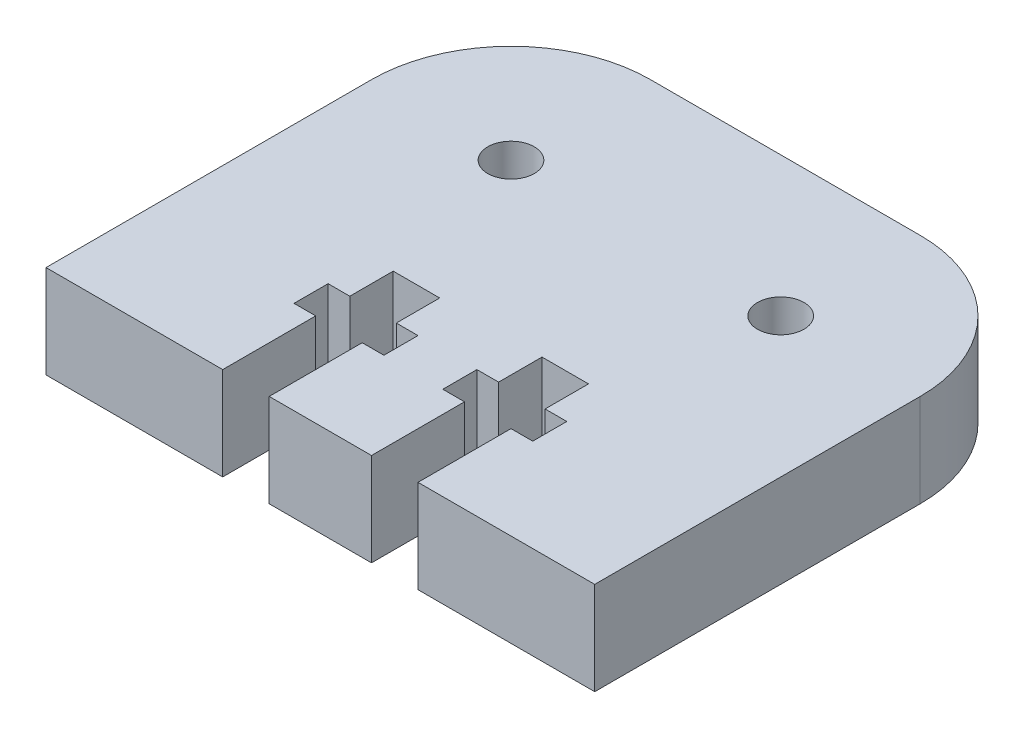
SolidWorks part; units mm, degrees
ref_plane "Front Plane" through (0, 0, 0) normal (0, 0, 1) x (1, 0, 0)
ref_plane "Top Plane" through (0, 0, 0) normal (0, 1, 0) x (1, 0, 0)
ref_plane "Right Plane" through (0, 0, 0) normal (1, 0, 0) x (0, 0, -1)
sketch "Sketch1" plane through (0, 0, 0) normal (0, 1, 0) x (1, 0, 0)
  line L0 (-55, 0) -> (55, 0) construction
  line L1 (-17.7, 15) -> (0, 15)
  line L2 (-17.7, 15) -> (-17.7, -15)
  line L3 (-17.7, -15) -> (-6.3, -15)
  line L4 (0, 15) -> (0, -15)
  line L5 (-17.7, 15) -> (0, -15) construction
  line L6 (-17.7, -15) -> (0, 15) construction
  line L7 (0, -55) -> (0, 55) construction
  line L8 (-4.8, -7.9) -> (-4.8, -4) construction
  line L9 (-6.3, -4) -> (-3.3, -4)
  line L10 (-6.3, -4) -> (-6.3, -6.8)
  line L12 (-3.3, -4) -> (-3.3, -6.8)
  line L13 (-6.3, -4) -> (-3.3, -15) construction
  line L14 (-6.3, -15) -> (-3.3, -4) construction
  line L15 (-7.7, -9) -> (-6.3, -9)
  line L16 (-7.7, -9) -> (-7.7, -6.8)
  line L17 (-7.7, -6.8) -> (-6.3, -6.8)
  line L18 (-1.9, -9) -> (-1.9, -6.8)
  line L19 (-7.7, -9) -> (-1.9, -6.8) construction
  line L20 (-7.7, -6.8) -> (-1.9, -9) construction
  line L21 (-3.3, -9) -> (-1.9, -9)
  line L22 (-3.3, -6.8) -> (-1.9, -6.8)
  line L23 (-3.3, -9) -> (-3.3, -15)
  line L24 (-6.3, -9) -> (-6.3, -15)
  line L26 (-3.3, -15) -> (0, -15)
  circle A0 centre (-8.7, 6) radius 1.5
  point P0 (-8.85, 0)
  point P10 (-4.8, -9.5)
  point P15 (-4.8, -7.9)
  dimension "D8" = 3
  dimension "D1" = 3
  dimension "D2" = 5.8
  dimension "D3" = 2.2
  dimension "D4" = 4.8
  dimension "D5" = 11
  dimension "D6" = 6
  dimension "D7" = 10
  dimension "D9" = 9
  dimension "D10" = 9
  dimension "D11" = 30
extrude "Boss-Extrude1" add sketch "Sketch1" along normal blind 6
mirror "Mirror1" about plane through (0, 6, -15) normal (-1, 0, 0) of bodies 101
fillet "Fillet1" radius 9 2 edges at (17.7, 3, -15) (-17.7, 3, -15)
equation "\"D4@Sketch1\"=9.6/2"
equation "\"D10@Sketch1\"=\"D9@Sketch1\""
equation "\"M3_d\"= \"M3_d_laser@troublemaker.Assembly\""
equation "\"housing_t\"= \"housing_t_glob@troublemaker.Assembly\""
equation "\"D1@Boss-Extrude1\"=\"housing_t\""
equation "\"D8@Sketch1\"=\"M3_d\""
equation "\"D1@Sketch1\"=\"M3_d\""
equation "\"M3_nut_m\"= \"M3_nut_m_glob@troublemaker.Assembly\""
equation "\"M3_nut_s\"= \"M3_nut_s_glob@troublemaker.Assembly\""
equation "\"housing_screws_l\"= \"housing_screws_l_glob@troublemaker.Assembly\""
equation "\"housing_nut_l\"= \"housing_nut_l_glob@troublemaker.Assembly\""
equation "\"D6@Sketch1\"=\"housing_nut_l\""
equation "\"D5@Sketch1\"=\"housing_screws_l\""
equation "\"D2@Sketch1\"=\"M3_nut_s\""
equation "\"D3@Sketch1\"=\"M3_nut_m\""
